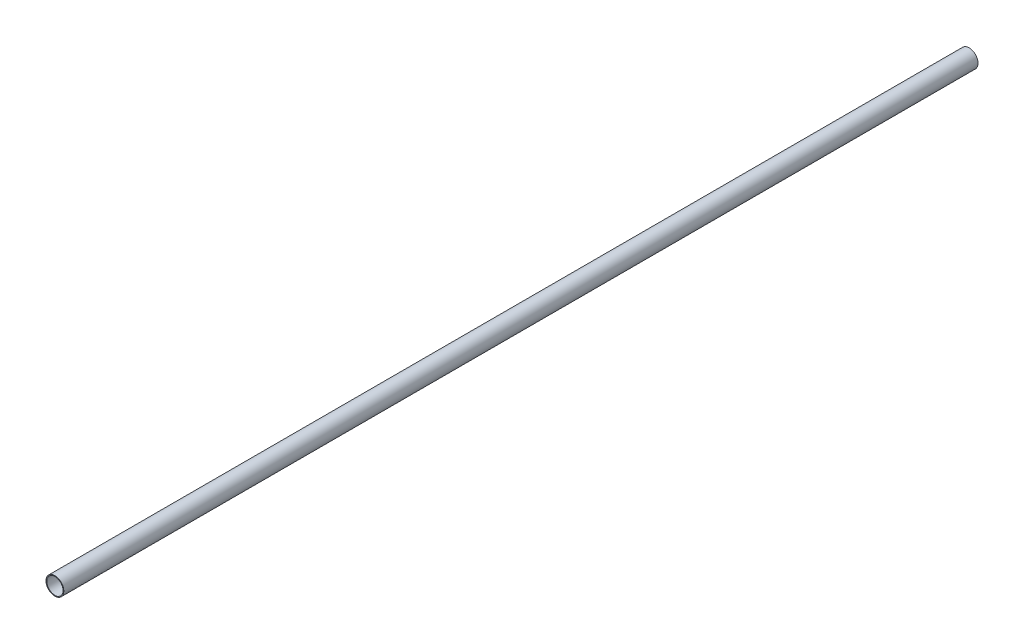
SolidWorks part; units mm, degrees
material "ASTM A36 Steel"
ref_plane "Front Plane" through (0, 0, 0) normal (0, 0, 1) x (1, 0, 0)
ref_plane "Top Plane" through (0, 0, 0) normal (0, 1, 0) x (1, 0, 0)
ref_plane "Right Plane" through (0, 0, 0) normal (1, 0, 0) x (0, 0, -1)
sketch "Sketch1" plane through (0, 0, 0) normal (0, 0, 1) x (1, 0, 0)
  circle A0 centre (0, 0) radius 84.1375
  circle A1 centre (0, 0) radius 77.0255
  dimension "D1" = 168.275
  dimension "D2" = 7.112
extrude "Boss-Extrude1" add sketch "Sketch1" along normal blind 8630
